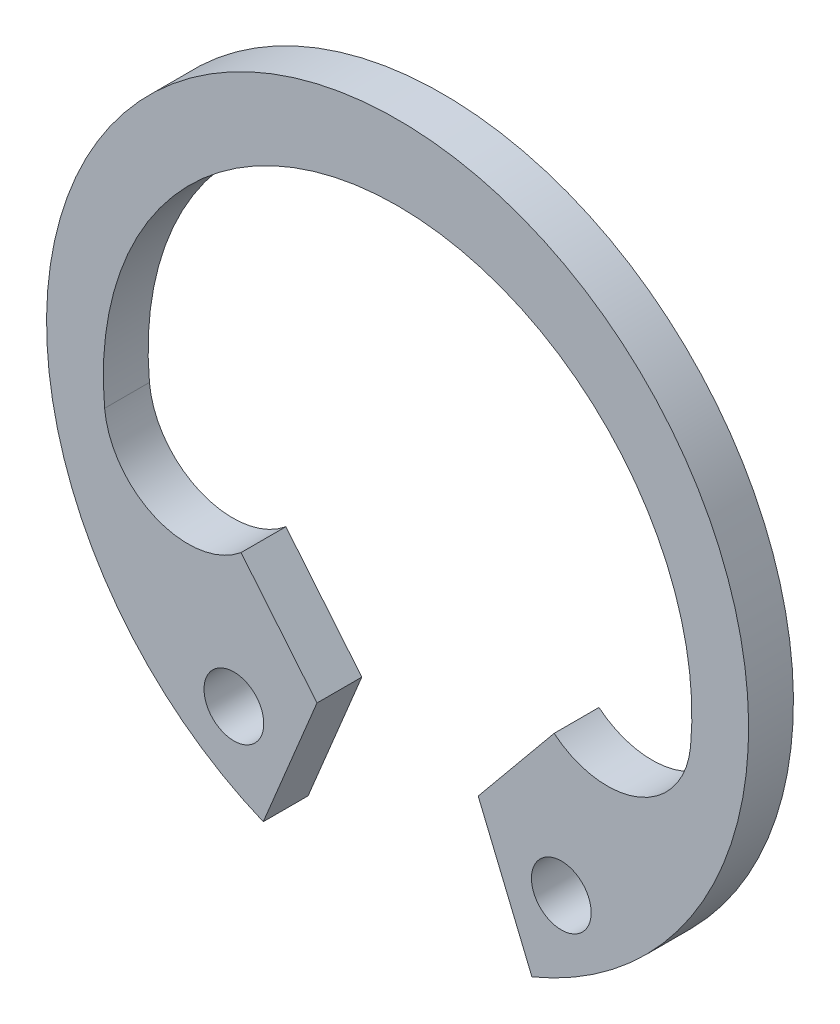
SolidWorks part; units mm, degrees
ref_plane "前视" through (0, 0, 0) normal (0, 0, 1) x (1, 0, 0)
ref_plane "上视" through (0, 0, 0) normal (0, 1, 0) x (1, 0, 0)
ref_plane "右视" through (0, 0, 0) normal (1, 0, 0) x (0, 0, -1)
sketch "草图1" plane through (0, 0, 0) normal (0, 0, 1) x (1, 0, 0)
  line L0 (0, -11.8766) -> (0, 11.8063) construction
  line L1 (0, 0) -> (-4.6199, -11.1535) construction
  line L2 (-5.2396, -3.4247) -> (-2.6979, -6.5134)
  line L3 (-2.6979, -6.5134) -> (-4.4965, -10.8556)
  line L4 (2.6979, -6.5134) -> (4.4965, -10.8556)
  line L5 (5.2396, -3.4247) -> (2.6979, -6.5134)
  arc A0 (4.4965, -10.8556) -> (-4.4965, -10.8556) centre (0, 0) ccw
  arc A1 (9.8064, -1.5258) -> (-9.8064, -1.5258) centre (0, -0.6) ccw
  circle A2 centre (-5.48, -8.0037) radius 1
  arc A3 (-9.8064, -1.5258) -> (-5.2396, -3.4247) centre (-7.0188, -1.2626) ccw
  circle A4 centre (5.48, -8.0037) radius 1
  arc A5 (9.8064, -1.5258) -> (5.2396, -3.4247) centre (7.0188, -1.2626) cw
  dimension "D1" = 23.5
  dimension "D2" = 19.7
  dimension "D4" = 2
  dimension "D5" = 2.8
  dimension "D3" = 0.6
  dimension "D6" = 4.7
  dimension "D7" = 4
  dimension "D8" = 22.5
  dimension "D9" = 9.7
  dimension "D10" = 2
sketch "尺寸草图" plane through (0, 0, 0) normal (0, 0, 1) x (1, 0, 0)
  line L0 (-11.75, 0) -> (11.75, 0) construction
  line L1 (0, 0) -> (31.8198, -31.8198) construction
  circle A2 centre (0, 0) radius 11.75
  point P9 (7.95, 0)
  point P10 (8.55, 0)
  point P11 (-6.9, 0)
  point P12 (-3.7, 0)
  point P13 (4.7, 0)
  point P14 (-7.7, 0)
  point P15 (-11.7, 0)
  point P16 (-9.7, 0)
  point P18 (1.0607, -1.0607)
  dimension "DD" = 23.5
  dimension "D2" = 45
  dimension "d" = 19.7
  dimension "c" = 0.6
  dimension "R" = 9.7
  dimension "d1" = 2
  dimension "B1" = 2
  dimension "aa" = 45
  dimension "a" = 4.7
  dimension "B" = 4
  dimension "R2" = 2.8
  dimension "s" = 1.5
extrude "基体-拉伸" add sketch "草图1" along normal blind 1.5
